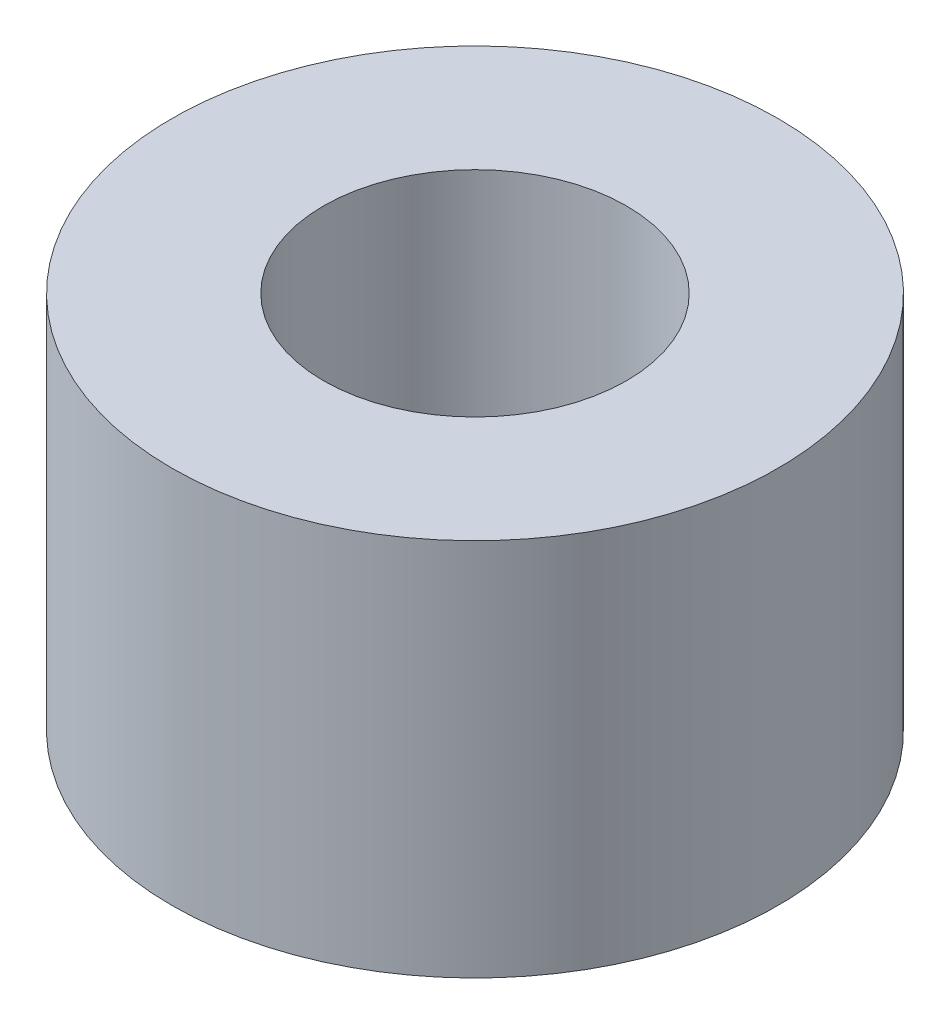
SolidWorks part; units mm, degrees
material "天然橡胶"
ref_plane "前视基准面" through (0, 0, 0) normal (0, 0, 1) x (1, 0, 0)
ref_plane "上视基准面" through (0, 0, 0) normal (0, 1, 0) x (1, 0, 0)
ref_plane "右视基准面" through (0, 0, 0) normal (1, 0, 0) x (0, 0, -1)
sketch "草图1" plane through (0, 0, 0) normal (0, 1, 0) x (1, 0, 0)
  circle A0 centre (0, 0) radius 4
  circle A1 centre (0, 0) radius 2
extrude "凸台-拉伸1" add sketch "草图1" along normal blind 5
